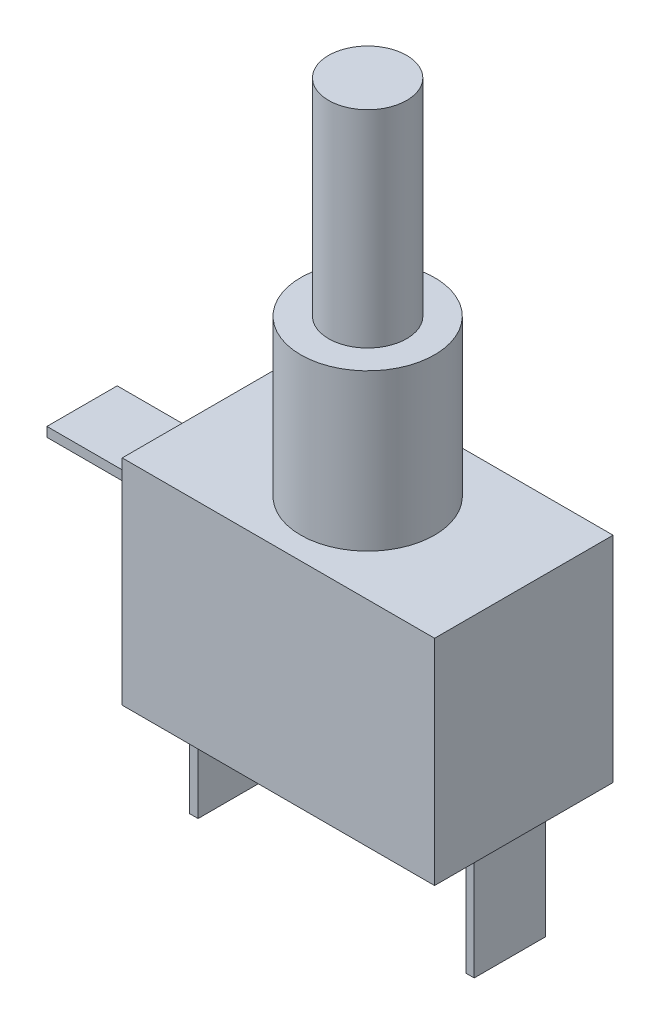
SolidWorks part; units mm, degrees
ref_plane "Front Plane" through (0, 0, 0) normal (0, 0, 1) x (1, 0, 0)
ref_plane "Top Plane" through (0, 0, 0) normal (0, 1, 0) x (1, 0, 0)
ref_plane "Right Plane" through (0, 0, 0) normal (1, 0, 0) x (0, 0, -1)
sketch "Sketch1" plane through (0, 0, 0) normal (0, 1, 0) x (1, 0, 0)
  line L1 (-28, 16) -> (0, 16)
  line L2 (-28, 16) -> (-28, 0)
  line L3 (-28, 0) -> (0, 0)
  line L4 (0, 16) -> (0, 0)
  dimension "D1" = 28
  dimension "D2" = 16
extrude "Boss-Extrude1" add sketch "Sketch1" along normal blind 19.2
sketch "Sketch2" plane through (0, 0, 0) normal (0, -1, 0) x (1, 0, 0)
  line L0 (-28, -8) -> (0, -8)
  line L1 (-2, -4.8) -> (-1.25, -4.8)
  line L2 (-2, -4.8) -> (-2, -11.2)
  line L3 (-2, -11.2) -> (-1.25, -11.2)
  line L4 (-1.25, -4.8) -> (-1.25, -11.2)
  line L5 (-26.75, -4.8) -> (-26, -4.8)
  line L6 (-26.75, -4.8) -> (-26.75, -11.2)
  line L7 (-26.75, -11.2) -> (-26, -11.2)
  line L8 (-26, -4.8) -> (-26, -11.2)
  line L9 (-28, -16) -> (-28, 0) construction
  line L10 (0, 0) -> (0, -16) construction
  line L11 (-26.75, -8) -> (-25.1023, -8)
  line L12 (-2, -8) -> (-1.4951, -8)
  dimension "D1" = 0
  dimension "D2" = 0
  dimension "D3" = 0.75
  dimension "D4" = 6.4
  dimension "D5" = 6.4
  dimension "D6" = 0.75
  dimension "D7" = 1.25
  dimension "D8" = 1.25
extrude "Boss-Extrude2" add sketch "Sketch2" along normal blind 10.2 contours L8 L7 L6 L5 | L2 L3 L4 L1
sketch "Sketch3" plane through (-28, 0, 0) normal (-1, 0, 0) x (0, 0, 1)
  line L0 (-16, 19.2) -> (-16, 0) construction
  line L1 (-1.7, 16.57) -> (-8, 16.57)
  line L2 (-1.7, 16.57) -> (-1.7, 15.72)
  line L3 (-1.7, 15.72) -> (-8, 15.72)
  line L4 (-8, 16.57) -> (-8, 15.72)
  line L5 (-16, 19.2) -> (0, 19.2) construction
  dimension "D1" = 6.3
  dimension "D2" = 0.85
  dimension "D3" = 8
  dimension "D4" = 2.63
extrude "Boss-Extrude3" add sketch "Sketch3" along normal blind 8.45
sketch "Sketch4" plane through (0, 19.2, 0) normal (0, 1, 0) x (1, 0, 0)
  line L0 (-28, 0) -> (0, 16)
  circle A0 centre (-14, 8) radius 6
  dimension "D1" = 12
extrude "Boss-Extrude4" add sketch "Sketch4" along normal blind 14 contours L0 A0 | L0 A0
sketch "Sketch5" plane through (0, 33.2, 0) normal (0, 1, 0) x (1, 0, 0)
  circle A0 centre (-14, 8) radius 3.5
  dimension "D1" = 7
extrude "Boss-Extrude5" add sketch "Sketch5" along normal blind 18.5
